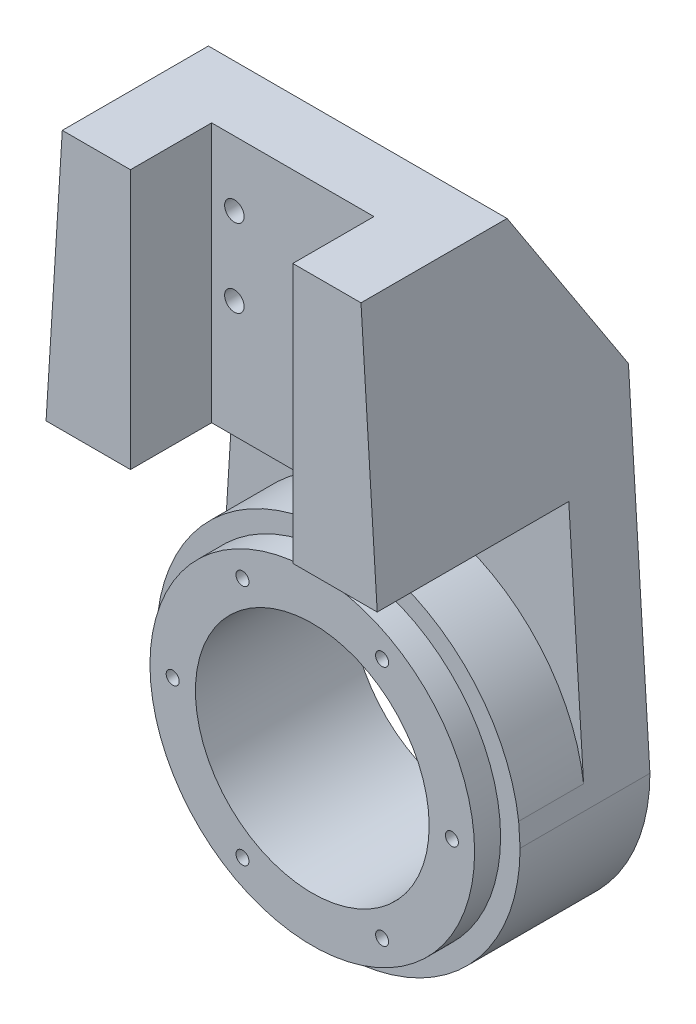
SolidWorks part; units mm, degrees
material "ABS"
ref_plane "Front Plane" through (0, 0, 0) normal (0, 0, 1) x (1, 0, 0)
ref_plane "Top Plane" through (0, 0, 0) normal (0, 1, 0) x (1, 0, 0)
ref_plane "Right Plane" through (0, 0, 0) normal (1, 0, 0) x (0, 0, -1)
sketch "Sketch1" plane through (0, 0, 0) normal (0, 0, 1) x (1, 0, 0)
  line L0 (0, 0) -> (0, 55.4418) construction
  line L3 (-28, 80) -> (28, 80)
  line L4 (-28, 80) -> (-28, 0)
  line L5 (28, 80) -> (28, 0)
  circle A0 centre (0, 0) radius 28
  circle A1 centre (0, 0) radius 18
  arc A3 (-28, 0) -> (28, 0) centre (0, 0) cw
  dimension "D1" = 28
  dimension "D2" = 36
  dimension "D3" = 56
  dimension "D4" = 56
  dimension "D5" = 80
extrude "Boss-Extrude1" add sketch "Sketch1" along normal blind 10
sketch "Sketch5" plane through (0, 0, 10) normal (0, 0, 1) x (1, 0, 0)
  circle A0 centre (0, 0) radius 18
  circle A1 centre (0, 0) radius 28
extrude "Boss-Extrude6" add sketch "Sketch5" along normal blind 10
sketch "Sketch6" plane through (0, 0, 20) normal (0, 0, 1) x (1, 0, 0)
  circle A0 centre (0, 0) radius 18
  circle A1 centre (0, 0) radius 25
extrude "Boss-Extrude7" add sketch "Sketch6" along normal blind 4
sketch "Sketch7" plane through (0, 0, 24) normal (0, 0, 1) x (1, 0, 0)
  line L0 (-57.3311, 0) -> (50.1031, 0) construction
  line L1 (25.2185, 43.6796) -> (0, 0) construction
  line L2 (0, 0) -> (-23.2928, -40.3443) construction
  line L3 (-23.2928, -40.3443) -> (0, 0) construction
  line L4 (-28.8082, 49.8973) -> (0, 0) construction
  line L5 (0, 0) -> (23.8679, -41.3404) construction
  circle A0 centre (0, 0) radius 21.5 construction
  circle A1 centre (-10.75, 18.6195) radius 1
  circle A2 centre (10.75, 18.6195) radius 1
  circle A3 centre (21.5, 0) radius 1
  circle A4 centre (10.75, -18.6195) radius 1
  circle A5 centre (-10.75, -18.6195) radius 1
  circle A6 centre (-21.5, 0) radius 1
  dimension "D3" = 43
  dimension "D1" = 60
  dimension "D2" = 60
extrude "Cut-Extrude1" cut sketch "Sketch7" against normal blind 24
sketch "Sketch8" plane through (0, 0, 10) normal (0, 0, 1) x (1, 0, 0)
  line L0 (-28, 80) -> (-28, 0) construction
  line L1 (28, 80) -> (28, 0) construction
  line L2 (-28, 40) -> (-28, 80)
  line L3 (-28, 80) -> (28, 80)
  line L4 (28, 80) -> (28, 40)
  line L5 (-28, 40) -> (28, 40)
  dimension "D1" = 40
extrude "Boss-Extrude8" add sketch "Sketch8" along normal blind 29.5
sketch "Sketch9" plane through (0, 80, 0) normal (0, 1, 0) x (1, 0, 0)
  line L0 (28, -39.5) -> (-28, -39.5) construction
  line L1 (-12.5, -39.5) -> (12.5, -39.5)
  line L2 (-12.5, -39.5) -> (-12.5, -27)
  line L3 (-12.5, -27) -> (12.5, -27)
  line L4 (12.5, -39.5) -> (12.5, -27)
  line L6 (28, -39.5) -> (28, 0) construction
  dimension "D1" = 15.5
  dimension "D2" = 25
  dimension "D3" = 12.5
extrude "Cut-Extrude2" cut sketch "Sketch9" against normal blind 45
sketch "Sketch10" plane through (0, 80, 0) normal (0, 1, 0) x (1, 0, 0)
  line L0 (-28, 0) -> (28, 0) construction
  line L2 (5, 0) -> (17, 0)
  line L3 (5, 0) -> (5, -17)
  line L4 (5, -17) -> (17, -17)
  line L5 (17, 0) -> (17, -17)
  line L6 (28, -39.5) -> (28, 0) construction
  line L9 (-17, 0) -> (-5, 0)
  line L10 (-17, 0) -> (-17, -17)
  line L11 (-17, -17) -> (-5, -17)
  line L12 (-5, 0) -> (-5, -17)
  dimension "D1" = 10
  dimension "D2" = 11
  dimension "D3" = 17
  dimension "D4" = 12
  dimension "D5" = 12
  dimension "D6" = 17
extrude "Cut-Extrude3" cut sketch "Sketch10" against normal blind 27
sketch "Sketch11" plane through (17, 0, 0) normal (-1, 0, 0) x (0, 0, 1)
  line L2 (0, 80) -> (0, 0) construction
  line L3 (0, 53) -> (17, 80)
  line L4 (17, 80) -> (0, 80)
  line L5 (0, 80) -> (0, 53)
extrude "Cut-Extrude4" cut sketch "Sketch11" against normal blind 16 and the other way blind 42
sketch "Sketch13" plane through (0, 0, 0) normal (0, 0, -1) x (-1, 0, 0)
  line L0 (28, 80) -> (28, 0)
  line L6 (28, 0) -> (23, 80)
  line L7 (25, 80) -> (17, 80) construction
  line L8 (23, 80) -> (28, 80)
  dimension "D1" = 5
  dimension "D2" = 80
extrude "Cut-Extrude5" cut sketch "Sketch13" against normal blind 40
mirror "Mirror1" about plane through (0, 0, 0) normal (1, 0, 0) of "Cut-Extrude5"
sketch "Sketch14" plane through (0, 0, 17) normal (0, 0, -1) x (-1, 0, 0)
  line L0 (-5, 80) -> (-17, 80) construction
  line L1 (-17, 53) -> (-5, 53) construction
  line L2 (17, 80) -> (5, 80) construction
  line L3 (17, 53) -> (5, 53) construction
  line L4 (-5, 53) -> (-5, 80) construction
  line L5 (5, 53) -> (5, 80) construction
  circle A0 centre (-9, 70) radius 1.5
  circle A1 centre (-9, 58) radius 1.5
  circle A2 centre (9, 70) radius 1.5
  circle A3 centre (9, 58) radius 1.5
  dimension "D1" = 3
  dimension "D2" = 3
  dimension "D3" = 3
  dimension "D4" = 3
  dimension "D5" = 10
  dimension "D6" = 5
  dimension "D7" = 10
  dimension "D8" = 5
  dimension "D9" = 4
  dimension "D10" = 4
  dimension "D11" = 4
  dimension "D12" = 4
extrude "Cut-Extrude6" cut sketch "Sketch14" against normal blind 10
